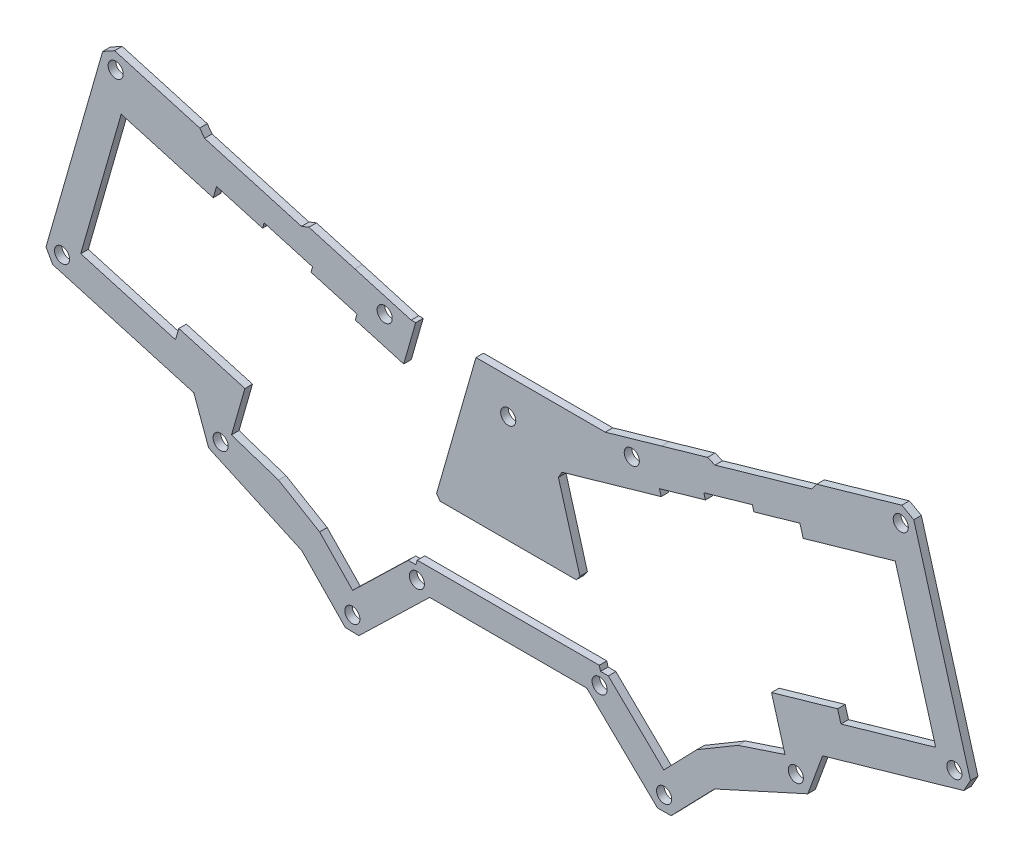
SolidWorks part; units mm, degrees
ref_plane "Plan de face" through (0, 0, 0) normal (0, 0, 1) x (1, 0, 0)
ref_plane "Plan de dessus" through (0, 0, 0) normal (0, 1, 0) x (1, 0, 0)
ref_plane "Plan de droite" through (0, 0, 0) normal (1, 0, 0) x (0, 0, -1)
sketch "Esquisse1" plane through (0, 0, 0) normal (0, 0, 1) x (1, 0, 0)
  line L0 (-121.6461, -32.0475) -> (-108.1875, -28.1884) construction
  line L1 (-108.1875, -28.1884) -> (-104.3283, -41.647) construction
  line L2 (-104.3283, -41.647) -> (-117.7869, -45.5062) construction
  line L3 (-117.7869, -45.5062) -> (-121.6461, -32.0475) construction
  line L4 (-100.1763, -37.9855) -> (-104.0355, -24.5269) construction
  line L5 (-104.0355, -24.5269) -> (-90.5769, -20.6677) construction
  line L6 (-90.5769, -20.6677) -> (-86.7177, -34.1263) construction
  line L7 (-86.7177, -34.1263) -> (-100.1763, -37.9855) construction
  line L8 (-82.5657, -30.4649) -> (-86.4249, -17.0063) construction
  line L9 (-86.4249, -17.0063) -> (-72.9663, -13.1471) construction
  line L10 (-72.9663, -13.1471) -> (-69.1071, -26.6057) construction
  line L11 (-69.1071, -26.6057) -> (-82.5657, -30.4649) construction
  line L12 (-63.6458, -27.5106) -> (-67.505, -14.0519) construction
  line L13 (-67.505, -14.0519) -> (-54.0463, -10.1927) construction
  line L14 (-54.0463, -10.1927) -> (-50.1872, -23.6514) construction
  line L15 (-50.1872, -23.6514) -> (-63.6458, -27.5106) construction
  line L16 (-44.0711, -26.8394) -> (-47.9303, -13.3808) construction
  line L17 (-47.9303, -13.3808) -> (-34.4717, -9.5216) construction
  line L18 (-34.4717, -9.5216) -> (-30.6125, -22.9802) construction
  line L19 (-30.6125, -22.9802) -> (-44.0711, -26.8394) construction
  line L20 (-25.8054, -21.6018) -> (-29.6646, -8.1432) construction
  line L21 (-29.6646, -8.1432) -> (-16.206, -4.284) construction
  line L22 (-16.206, -4.284) -> (-12.3468, -17.7426) construction
  line L23 (-12.3468, -17.7426) -> (-25.8054, -21.6018) construction
  line L24 (-116.4086, -50.3128) -> (-102.95, -46.4536) construction
  line L25 (-102.95, -46.4536) -> (-99.0908, -59.9122) construction
  line L26 (-99.0908, -59.9122) -> (-112.5494, -63.7714) construction
  line L27 (-112.5494, -63.7714) -> (-116.4086, -50.3128) construction
  line L28 (-98.798, -42.7922) -> (-85.3394, -38.933) construction
  line L29 (-85.3394, -38.933) -> (-81.4802, -52.3916) construction
  line L30 (-81.4802, -52.3916) -> (-94.9388, -56.2508) construction
  line L31 (-94.9388, -56.2508) -> (-98.798, -42.7922) construction
  line L32 (-81.1874, -35.2715) -> (-67.7288, -31.4123) construction
  line L33 (-67.7288, -31.4123) -> (-63.8696, -44.8709) construction
  line L34 (-63.8696, -44.8709) -> (-77.3282, -48.7301) construction
  line L35 (-77.3282, -48.7301) -> (-81.1874, -35.2715) construction
  line L36 (-62.2675, -32.3172) -> (-48.8089, -28.458) construction
  line L37 (-48.8089, -28.458) -> (-44.9497, -41.9166) construction
  line L38 (-44.9497, -41.9166) -> (-58.4083, -45.7758) construction
  line L39 (-58.4083, -45.7758) -> (-62.2675, -32.3172) construction
  line L40 (-42.6928, -31.646) -> (-29.2342, -27.7869) construction
  line L41 (-29.2342, -27.7869) -> (-25.375, -41.2455) construction
  line L42 (-25.375, -41.2455) -> (-38.8336, -45.1047) construction
  line L43 (-38.8336, -45.1047) -> (-42.6928, -31.646) construction
  line L44 (-24.4271, -26.4084) -> (-10.9685, -22.5492) construction
  line L45 (-10.9685, -22.5492) -> (-7.1093, -36.0078) construction
  line L46 (-7.1093, -36.0078) -> (-20.5679, -39.867) construction
  line L47 (-20.5679, -39.867) -> (-24.4271, -26.4084) construction
  line L48 (-19.1896, -44.6737) -> (-5.731, -40.8145) construction
  line L49 (-5.731, -40.8145) -> (-1.8718, -54.2731) construction
  line L50 (-1.8718, -54.2731) -> (-15.3304, -58.1323) construction
  line L51 (-15.3304, -58.1323) -> (-19.1896, -44.6737) construction
  line L52 (-37.4554, -49.9113) -> (-23.9967, -46.0521) construction
  line L53 (-23.9967, -46.0521) -> (-20.1376, -59.5107) construction
  line L54 (-20.1376, -59.5107) -> (-33.5962, -63.3699) construction
  line L55 (-33.5962, -63.3699) -> (-37.4554, -49.9113) construction
  line L56 (-57.03, -50.5825) -> (-43.5714, -46.7233) construction
  line L57 (-43.5714, -46.7233) -> (-39.7122, -60.1819) construction
  line L58 (-39.7122, -60.1819) -> (-53.1708, -64.0411) construction
  line L59 (-53.1708, -64.0411) -> (-57.03, -50.5825) construction
  line L60 (-75.9499, -53.5368) -> (-62.4913, -49.6776) construction
  line L61 (-62.4913, -49.6776) -> (-58.6321, -63.1362) construction
  line L62 (-58.6321, -63.1362) -> (-72.0908, -66.9954) construction
  line L63 (-72.0908, -66.9954) -> (-75.9499, -53.5368) construction
  line L64 (-93.5605, -61.0574) -> (-80.1019, -57.1982) construction
  line L65 (-80.1019, -57.1982) -> (-76.2427, -70.6569) construction
  line L66 (-76.2427, -70.6569) -> (-89.7013, -74.516) construction
  line L67 (-89.7013, -74.516) -> (-93.5605, -61.0574) construction
  line L68 (-111.1711, -68.5781) -> (-97.7125, -64.7189) construction
  line L69 (-97.7125, -64.7189) -> (-93.8533, -78.1775) construction
  line L70 (-93.8533, -78.1775) -> (-107.3119, -82.0367) construction
  line L71 (-107.3119, -82.0367) -> (-111.1711, -68.5781) construction
  line L72 (-79.0181, -77.3048) -> (-65.5595, -73.4456) construction
  line L73 (-65.5595, -73.4456) -> (-61.7003, -86.9042) construction
  line L74 (-61.7003, -86.9042) -> (-75.1589, -90.7634) construction
  line L75 (-75.1589, -90.7634) -> (-79.0181, -77.3048) construction
  line L76 (-99.4001, -88.1351) -> (-87.3916, -80.9362)
  line L77 (-87.3916, -80.9362) -> (-80.1927, -92.9448)
  line L78 (-80.1927, -92.9448) -> (-92.2012, -100.1436)
  line L79 (-92.2012, -100.1436) -> (-99.4001, -88.1351)
  line L80 (-120.0498, -100.4367) -> (-110.317, -90.3719)
  line L81 (-110.317, -90.3719) -> (-100.2522, -100.1047)
  line L82 (-100.2522, -100.1047) -> (-109.985, -110.1695)
  line L83 (-109.985, -110.1695) -> (-120.0498, -100.4367)
  line L86 (0.634, -55.7756) -> (-52.9527, -71.1413) construction
  line L89 (-59.2205, -88.2424) -> (-52.9527, -71.1413) construction
  line L96 (-93.4066, -103.0586) -> (-59.4637, -88.3612) construction
  line L97 (-105.418, -115.2057) -> (-93.9754, -103.3509) construction
  line L98 (-126.5332, -96.9919) -> (-107.5003, -115.385) construction
  line L99 (-167.7972, -50.1766) -> (-183.2082, -64.014) construction
  line L100 (-106.3822, -25.4572) -> (-123.6848, -30.4187) construction
  line L101 (-72.1178, -10.6906) -> (-88.4663, -15.3784) construction
  line L102 (-53.2337, -7.6163) -> (-70.5393, -12.5786) construction
  line L103 (-33.6604, -6.9452) -> (-50.9661, -11.9075) construction
  line L104 (-15.3965, -1.7081) -> (-31.745, -6.396) construction
  line L105 (0.5403, -55.2132) -> (-14.6896, -2.0999) construction
  line L106 (-16.199, -60.6113) -> (0.1495, -55.9235) construction
  line L107 (-52.7198, -71.0835) -> (-18.1144, -61.1606) construction
  line L108 (-59.1184, -88.0534) -> (-52.9674, -71.2752) construction
  line L109 (-183.2082, -64.014) -> (-173.1824, -64.9357) construction
  line L113 (-102.2678, -134.438) -> (-84.7238, -116.3191) construction
  line L114 (-84.7238, -116.3191) -> (-47.2969, -99.2981) construction
  line L115 (-47.2969, -99.2981) -> (-41.4917, -83.4594) construction
  line L116 (14.3812, -67.4381) -> (-41.4917, -83.4594) construction
  line L117 (17.8093, -61.2536) -> (-5.1371, 18.7701) construction
  line L122 (-11.3217, 22.1985) -> (-107.4545, -5.3614) construction
  line L129 (-167.7953, -27.6055) -> (-167.7953, -64.7189) construction
  line L130 (-242.0685, -103.8419) -> (-276.37, -88.2424) construction
  line L131 (-229.5108, -116.8112) -> (-242.0685, -103.8419) construction
  line L138 (-208.9328, -96.8551) -> (-229.5108, -116.8112) construction
  line L139 (-225.5107, -79.6567) -> (-208.9328, -96.8551) construction
  line L140 (-109.3352, -134.5492) -> (-102.2678, -134.438) construction
  line L142 (-5.1371, 18.7701) -> (-11.3217, 22.1985) construction
  line L143 (-211.4691, -30.6868) -> (-225.5107, -79.6567) construction
  line L147 (-114.18, -7.2899) -> (-107.4545, -5.3614) construction
  line L148 (-114.18, -7.2899) -> (-123.7936, -10.0465) construction
  line L154 (-118.7579, -16.9241) -> (-12.0005, 13.6817) construction
  line L155 (-131.531, -101.8802) -> (-105.9239, -126.7133) construction
  line L156 (-105.9239, -126.7133) -> (-89.4162, -109.6646) construction
  line L157 (-128.0696, -96.8789) -> (-106.0575, -118.2258)
  line L158 (-106.0575, -118.2258) -> (-92.9354, -104.6737)
  line L161 (1.8709, -56.4612) -> (-35.7408, -67.2462)
  line L162 (1.8709, -56.4612) -> (-14.1861, -0.4639)
  line L163 (-14.1861, -0.4639) -> (-50.7166, -10.9388)
  line L164 (-50.7166, -10.9388) -> (-52.026, -6.3725)
  line L165 (-52.026, -6.3725) -> (-70.2913, -11.61)
  line L166 (-70.2913, -11.61) -> (-70.911, -9.4488)
  line L167 (-70.911, -9.4488) -> (-90.1377, -14.9608)
  line L168 (-90.1377, -14.9608) -> (-89.5177, -17.1231)
  line L169 (-89.5177, -17.1231) -> (-107.783, -22.3606)
  line L170 (-107.783, -22.3606) -> (-107.0938, -24.7639)
  line L171 (-107.0938, -24.7639) -> (-146.5019, -36.064)
  line L174 (-89.4162, -109.6646) -> (-53.6562, -93.4017) construction
  line L175 (-53.6562, -93.4017) -> (-47.6042, -76.8897) construction
  line L176 (9.2923, -60.5749) -> (-47.6042, -76.8897) construction
  line L177 (9.2923, -60.5749) -> (-12.0005, 13.6817) construction
  line L178 (-229.7336, -25.4495) -> (-211.4691, -30.6868) construction
  line L179 (-229.0444, -23.0462) -> (-229.7336, -25.4495) construction
  line L180 (-173.1824, -64.9357) -> (-167.7972, -60.1004) construction
  line L181 (-247.3097, -17.8087) -> (-229.0444, -23.0462) construction
  line L185 (17.8093, -61.2536) -> (14.3812, -67.4381) construction
  line L186 (-183.2987, -65.7677) -> (-173.2729, -66.6895) construction
  line L187 (-173.2729, -66.6895) -> (-167.8052, -74.7882) construction
  line L190 (-246.6897, -15.6465) -> (-247.3097, -17.8087) construction
  line L191 (-263.9939, -10.6857) -> (-246.6897, -15.6465) construction
  line L192 (-264.6136, -12.8469) -> (-263.9939, -10.6857) construction
  line L193 (-282.8789, -7.6094) -> (-264.6136, -12.8469) construction
  line L194 (-284.1883, -12.1757) -> (-282.8789, -7.6094) construction
  line L195 (-320.7188, -1.7008) -> (-284.1883, -12.1757) construction
  line L196 (-336.2245, -55.7756) -> (-320.7188, -1.7008) construction
  line L197 (-183.2987, -65.7677) -> (-167.8052, -88.0782) construction
  line L198 (-181.8414, -71.5322) -> (-174.8684, -81.0171) construction
  line L199 (-174.8684, -81.0171) -> (-178.3549, -83.9622) construction
  line L200 (-344.8828, -60.5749) -> (-323.5901, 13.6817) construction
  line L201 (-344.8828, -60.5749) -> (-287.9863, -76.8897) construction
  line L202 (-281.9343, -93.4017) -> (-287.9863, -76.8897) construction
  line L203 (-246.1743, -109.6646) -> (-281.9343, -93.4017) construction
  line L206 (-228.4967, -24.7639) -> (-209.2751, -30.2756)
  line L207 (-227.8075, -22.3606) -> (-228.4967, -24.7639)
  line L208 (-246.0728, -17.1231) -> (-227.8075, -22.3606)
  line L209 (-245.4528, -14.9608) -> (-246.0728, -17.1231)
  line L210 (-264.6796, -9.4488) -> (-245.4528, -14.9608)
  line L211 (-265.2993, -11.61) -> (-264.6796, -9.4488)
  line L212 (-283.5645, -6.3725) -> (-265.2993, -11.61)
  line L213 (-284.8739, -10.9388) -> (-283.5645, -6.3725)
  line L217 (0.634, -55.7756) -> (-14.8717, -1.7008) construction
  line L220 (-14.8717, -1.7008) -> (-51.4022, -12.1757) construction
  line L221 (-51.4022, -12.1757) -> (-52.7116, -7.6094) construction
  line L222 (-52.7116, -7.6094) -> (-70.9769, -12.8469) construction
  line L223 (-70.9769, -12.8469) -> (-71.5966, -10.6857) construction
  line L224 (-71.5966, -10.6857) -> (-88.9008, -15.6465) construction
  line L225 (-88.9008, -15.6465) -> (-88.2808, -17.8087) construction
  line L226 (-88.2808, -17.8087) -> (-106.5461, -23.0462) construction
  line L227 (-106.5461, -23.0462) -> (-105.8569, -25.4495) construction
  line L228 (-105.8569, -25.4495) -> (-124.1214, -30.6868) construction
  line L231 (-124.1214, -30.6868) -> (-110.0799, -79.6567) construction
  line L232 (-110.0799, -79.6567) -> (-126.6577, -96.8551) construction
  line L233 (-126.6577, -96.8551) -> (-106.0797, -116.8112) construction
  line L234 (-106.0797, -116.8112) -> (-93.522, -103.8419) construction
  line L235 (-93.522, -103.8419) -> (-59.2205, -88.2424) construction
  line L236 (-321.4044, -0.4639) -> (-284.8739, -10.9388)
  line L237 (-337.4614, -56.4612) -> (-321.4044, -0.4639)
  line L238 (-337.4614, -56.4612) -> (-299.8497, -67.2462)
  line L241 (-229.5331, -118.2258) -> (-242.6551, -104.6737)
  line L242 (-208.2366, -97.573) -> (-229.5331, -118.2258)
  line L243 (-229.6666, -126.7133) -> (-246.1743, -109.6646) construction
  line L244 (-204.0596, -101.8802) -> (-229.6666, -126.7133) construction
  line L245 (-331.2803, 15.8863) -> (-208.2299, -19.3904) construction
  line L246 (-178.3549, -83.9622) -> (-185.8788, -75.0552) construction
  line L247 (-185.8788, -75.0552) -> (-181.8414, -71.5322) construction
  line L248 (-176.7625, -46.6332) -> (-185.5498, -54.5291) construction
  line L249 (-185.5498, -54.5291) -> (-181.1562, -59.4188) construction
  line L250 (-181.1562, -59.4188) -> (-172.3689, -51.5229) construction
  line L251 (-276.4721, -88.0534) -> (-282.6232, -71.2752) construction
  line L252 (-282.8707, -71.0835) -> (-317.4761, -61.1606) construction
  line L253 (-319.3915, -60.6113) -> (-335.74, -55.9235) construction
  line L254 (-336.1309, -55.2132) -> (-320.9009, -2.0999) construction
  line L255 (-320.194, -1.7081) -> (-303.8455, -6.396) construction
  line L256 (-301.9301, -6.9452) -> (-284.6245, -11.9075) construction
  line L257 (-282.3568, -7.6163) -> (-265.0512, -12.5786) construction
  line L258 (-263.4727, -10.6906) -> (-247.1242, -15.3784) construction
  line L259 (-229.2083, -25.4572) -> (-211.9057, -30.4187) construction
  line L260 (-172.3689, -51.5229) -> (-176.7625, -46.6332) construction
  line L261 (-209.0573, -96.9919) -> (-228.0902, -115.385) construction
  line L262 (-230.1725, -115.2057) -> (-241.6151, -103.3509) construction
  line L263 (-242.1839, -103.0586) -> (-276.1268, -88.3612) construction
  line L264 (-276.37, -88.2424) -> (-282.6379, -71.1413) construction
  line L265 (-336.2245, -55.7756) -> (-282.6379, -71.1413) construction
  line L268 (-353.3998, -61.2536) -> (-349.9717, -67.4381) construction
  line L274 (-221.4105, -7.2899) -> (-206.0252, -11.7015) construction
  line L275 (-221.4105, -7.2899) -> (-228.136, -5.3614) construction
  line L276 (-330.4534, 18.7701) -> (-324.2688, 22.1985) construction
  line L277 (-226.2553, -134.5492) -> (-233.3227, -134.438) construction
  line L281 (-324.2688, 22.1985) -> (-228.136, -5.3614) construction
  line L282 (-353.3998, -61.2536) -> (-330.4534, 18.7701) construction
  line L283 (-349.9717, -67.4381) -> (-294.0988, -83.4594) construction
  line L284 (-288.2936, -99.2981) -> (-294.0988, -83.4594) construction
  line L285 (-250.8667, -116.3191) -> (-288.2936, -99.2981) construction
  line L286 (-233.3227, -134.438) -> (-250.8667, -116.3191) construction
  line L288 (-225.6055, -110.1695) -> (-215.5407, -100.4367) construction
  line L289 (-235.3383, -100.1047) -> (-225.6055, -110.1695) construction
  line L290 (-225.2735, -90.3719) -> (-235.3383, -100.1047) construction
  line L291 (-215.5407, -100.4367) -> (-225.2735, -90.3719) construction
  line L292 (-243.3893, -100.1436) -> (-236.1904, -88.1351) construction
  line L293 (-255.3978, -92.9448) -> (-243.3893, -100.1436) construction
  line L294 (-248.1989, -80.9362) -> (-255.3978, -92.9448) construction
  line L295 (-236.1904, -88.1351) -> (-248.1989, -80.9362) construction
  line L296 (-260.4316, -90.7634) -> (-256.5724, -77.3048) construction
  line L297 (-273.8902, -86.9042) -> (-260.4316, -90.7634) construction
  line L298 (-270.031, -73.4456) -> (-273.8902, -86.9042) construction
  line L299 (-256.5724, -77.3048) -> (-270.031, -73.4456) construction
  line L300 (-228.2786, -82.0367) -> (-224.4194, -68.5781) construction
  line L301 (-241.7372, -78.1775) -> (-228.2786, -82.0367) construction
  line L302 (-237.878, -64.7189) -> (-241.7372, -78.1775) construction
  line L303 (-224.4194, -68.5781) -> (-237.878, -64.7189) construction
  line L304 (-245.8892, -74.516) -> (-242.03, -61.0574) construction
  line L305 (-259.3478, -70.6569) -> (-245.8892, -74.516) construction
  line L306 (-255.4886, -57.1982) -> (-259.3478, -70.6569) construction
  line L307 (-242.03, -61.0574) -> (-255.4886, -57.1982) construction
  line L308 (-263.4998, -66.9954) -> (-259.6406, -53.5368) construction
  line L309 (-276.9584, -63.1362) -> (-263.4998, -66.9954) construction
  line L310 (-273.0992, -49.6776) -> (-276.9584, -63.1362) construction
  line L311 (-259.6406, -53.5368) -> (-273.0992, -49.6776) construction
  line L312 (-282.4197, -64.0411) -> (-278.5605, -50.5825) construction
  line L313 (-295.8783, -60.1819) -> (-282.4197, -64.0411) construction
  line L314 (-292.0191, -46.7233) -> (-295.8783, -60.1819) construction
  line L315 (-278.5605, -50.5825) -> (-292.0191, -46.7233) construction
  line L316 (-301.9944, -63.3699) -> (-298.1352, -49.9113) construction
  line L317 (-315.453, -59.5107) -> (-301.9944, -63.3699) construction
  line L318 (-311.5938, -46.0521) -> (-315.453, -59.5107) construction
  line L319 (-298.1352, -49.9113) -> (-311.5938, -46.0521) construction
  line L320 (-320.2601, -58.1323) -> (-316.4009, -44.6737) construction
  line L321 (-333.7187, -54.2731) -> (-320.2601, -58.1323) construction
  line L322 (-329.8595, -40.8145) -> (-333.7187, -54.2731) construction
  line L323 (-316.4009, -44.6737) -> (-329.8595, -40.8145) construction
  line L324 (-315.0226, -39.867) -> (-311.1634, -26.4084) construction
  line L325 (-328.4812, -36.0078) -> (-315.0226, -39.867) construction
  line L326 (-324.622, -22.5492) -> (-328.4812, -36.0078) construction
  line L327 (-311.1634, -26.4084) -> (-324.622, -22.5492) construction
  line L328 (-296.7569, -45.1047) -> (-292.8977, -31.646) construction
  line L329 (-310.2155, -41.2455) -> (-296.7569, -45.1047) construction
  line L330 (-306.3563, -27.7869) -> (-310.2155, -41.2455) construction
  line L331 (-292.8977, -31.646) -> (-306.3563, -27.7869) construction
  line L332 (-277.1822, -45.7758) -> (-273.323, -32.3172) construction
  line L333 (-290.6408, -41.9166) -> (-277.1822, -45.7758) construction
  line L334 (-286.7817, -28.458) -> (-290.6408, -41.9166) construction
  line L335 (-273.323, -32.3172) -> (-286.7817, -28.458) construction
  line L336 (-258.2623, -48.7301) -> (-254.4031, -35.2715) construction
  line L337 (-271.7209, -44.8709) -> (-258.2623, -48.7301) construction
  line L338 (-267.8617, -31.4123) -> (-271.7209, -44.8709) construction
  line L339 (-254.4031, -35.2715) -> (-267.8617, -31.4123) construction
  line L340 (-240.6517, -56.2508) -> (-236.7925, -42.7922) construction
  line L341 (-254.1103, -52.3916) -> (-240.6517, -56.2508) construction
  line L342 (-250.2511, -38.933) -> (-254.1103, -52.3916) construction
  line L343 (-236.7925, -42.7922) -> (-250.2511, -38.933) construction
  line L344 (-223.0411, -63.7714) -> (-219.1819, -50.3128) construction
  line L345 (-236.4997, -59.9122) -> (-223.0411, -63.7714) construction
  line L346 (-232.6405, -46.4536) -> (-236.4997, -59.9122) construction
  line L347 (-219.1819, -50.3128) -> (-232.6405, -46.4536) construction
  line L348 (-323.2438, -17.7426) -> (-309.7851, -21.6018) construction
  line L349 (-319.3846, -4.284) -> (-323.2438, -17.7426) construction
  line L350 (-305.926, -8.1432) -> (-319.3846, -4.284) construction
  line L351 (-309.7851, -21.6018) -> (-305.926, -8.1432) construction
  line L352 (-304.978, -22.9802) -> (-291.5194, -26.8394) construction
  line L353 (-301.1188, -9.5216) -> (-304.978, -22.9802) construction
  line L354 (-287.6602, -13.3808) -> (-301.1188, -9.5216) construction
  line L355 (-291.5194, -26.8394) -> (-287.6602, -13.3808) construction
  line L356 (-285.4034, -23.6514) -> (-271.9448, -27.5106) construction
  line L357 (-281.5442, -10.1927) -> (-285.4034, -23.6514) construction
  line L358 (-268.0856, -14.0519) -> (-281.5442, -10.1927) construction
  line L359 (-271.9448, -27.5106) -> (-268.0856, -14.0519) construction
  line L360 (-266.4834, -26.6057) -> (-253.0248, -30.4649) construction
  line L361 (-262.6242, -13.1471) -> (-266.4834, -26.6057) construction
  line L362 (-249.1656, -17.0063) -> (-262.6242, -13.1471) construction
  line L363 (-253.0248, -30.4649) -> (-249.1656, -17.0063) construction
  line L364 (-248.8728, -34.1263) -> (-235.4142, -37.9855) construction
  line L365 (-245.0136, -20.6677) -> (-248.8728, -34.1263) construction
  line L366 (-231.555, -24.5269) -> (-245.0136, -20.6677) construction
  line L367 (-235.4142, -37.9855) -> (-231.555, -24.5269) construction
  line L368 (-217.8036, -45.5062) -> (-213.9444, -32.0475) construction
  line L369 (-231.2622, -41.647) -> (-217.8036, -45.5062) construction
  line L370 (-227.4031, -28.1884) -> (-231.2622, -41.647) construction
  line L371 (-213.9444, -32.0475) -> (-227.4031, -28.1884) construction
  line L372 (-226.2553, -134.5492) -> (-194.0347, -103.3509) construction
  line L373 (-109.3352, -134.5492) -> (-141.5559, -103.3509) construction
  line L374 (-141.5559, -103.3509) -> (-194.0347, -103.3509) construction
  line L375 (-167.7972, -50.1766) -> (-152.3861, -64.014) construction
  line L376 (-162.4119, -64.9357) -> (-167.7972, -60.1004) construction
  line L377 (-162.3376, -66.6895) -> (-167.8052, -74.7882) construction
  line L378 (-152.3118, -65.7677) -> (-167.8052, -88.0782) construction
  line L379 (-163.2254, -51.5229) -> (-158.8318, -46.6332) construction
  line L380 (-154.4381, -59.4188) -> (-163.2254, -51.5229) construction
  line L381 (-150.0445, -54.5291) -> (-154.4381, -59.4188) construction
  line L382 (-158.8318, -46.6332) -> (-150.0445, -54.5291) construction
  line L383 (-149.7316, -75.0552) -> (-153.7691, -71.5322) construction
  line L384 (-157.2555, -83.9622) -> (-149.7316, -75.0552) construction
  line L385 (-160.742, -81.0171) -> (-157.2555, -83.9622) construction
  line L386 (-153.7691, -71.5322) -> (-160.742, -81.0171) construction
  line L387 (-152.3118, -65.7677) -> (-162.3376, -66.6895) construction
  line L388 (-152.3861, -64.014) -> (-162.4119, -64.9357) construction
  line L389 (-206.0252, -11.7015) -> (-129.5654, -11.7015) construction
  line L391 (-209.2751, -30.2756) -> (-204.5226, -13.7015)
  line L394 (-167.1758, -11.7015) -> (-206.0252, -11.7015) construction
  line L395 (-164.5217, -13.7015) -> (-167.1758, -11.7015) construction
  line L396 (-123.7936, -10.0465) -> (-130.6498, -22.4155) construction
  line L399 (-129.5654, -11.7015) -> (-123.7936, -10.0465) construction
  line L400 (-165.8487, -12.7015) -> (-206.1657, -12.7015) construction
  line L401 (-221.6861, -8.2511) -> (-206.1657, -12.7015) construction
  line L402 (-221.6861, -8.2511) -> (-228.4116, -6.3226) construction
  line L403 (-324.1462, 21.1231) -> (-228.4116, -6.3226) construction
  line L404 (-329.6063, 18.0963) -> (-324.1462, 21.1231) construction
  line L405 (-352.3244, -61.1311) -> (-329.6063, 18.0963) construction
  line L406 (-352.3244, -61.1311) -> (-349.2979, -66.591) construction
  line L407 (-349.2979, -66.591) -> (-293.3347, -82.6382) construction
  line L408 (-287.4987, -98.561) -> (-293.3347, -82.6382) construction
  line L409 (-250.2802, -115.4872) -> (-287.4987, -98.561) construction
  line L410 (-232.8926, -133.4446) -> (-250.2802, -115.4872) construction
  line L411 (-226.6535, -133.5428) -> (-232.8926, -133.4446) construction
  line L412 (-226.6535, -133.5428) -> (-194.4395, -102.3509) construction
  line L413 (-141.1511, -102.3509) -> (-194.4395, -102.3509) construction
  line L414 (-108.937, -133.5428) -> (-141.1511, -102.3509) construction
  line L415 (-108.937, -133.5428) -> (-102.6979, -133.4446) construction
  line L416 (-102.6979, -133.4446) -> (-85.3104, -115.4872) construction
  line L417 (-85.3104, -115.4872) -> (-48.0918, -98.561) construction
  line L418 (-48.0918, -98.561) -> (-42.2558, -82.6382) construction
  line L419 (13.7074, -66.591) -> (-42.2558, -82.6382) construction
  line L420 (16.7339, -61.1311) -> (13.7074, -66.591) construction
  line L421 (16.7339, -61.1311) -> (-5.9842, 18.0963) construction
  line L422 (-5.9842, 18.0963) -> (-11.4443, 21.1231) construction
  line L423 (-11.4443, 21.1231) -> (-107.1789, -6.3226) construction
  line L424 (-113.9044, -8.2511) -> (-107.1789, -6.3226) construction
  line L425 (-113.9044, -8.2511) -> (-124.4792, -11.2834) construction
  line L426 (-167.1758, -12.7015) -> (-206.1657, -12.7015) construction
  line L427 (-113.9044, -8.2511) -> (-123.5179, -11.0078) construction
  line L428 (-165.8487, -12.7015) -> (-154.4194, -21.3141) construction
  line L429 (-130.6498, -22.4155) -> (-124.4792, -11.2834) construction
  line L430 (-208.2366, -97.573) -> (-207.4919, -96.8551)
  line L433 (-221.9618, -9.2124) -> (-206.3062, -13.7015)
  line L434 (-129.2843, -13.7015) -> (-180.5957, -13.7015)
  line L435 (-166.1833, -13.7015) -> (-155.2884, -21.9114) construction
  line L436 (-141.5897, -69.6845) -> (-155.2884, -21.9114) construction
  line L437 (-138.3914, -71.4574) -> (-141.5897, -69.6845) construction
  line L438 (-119.7682, -66.1172) -> (-138.3914, -71.4574) construction
  line L439 (-117.9954, -62.9189) -> (-119.7682, -66.1172) construction
  line L440 (-117.9954, -62.9189) -> (-129.5744, -22.538) construction
  line L441 (-129.5744, -22.538) -> (-123.8054, -12.1305) construction
  line L442 (-113.6287, -9.2124) -> (-129.2843, -13.7015)
  line L443 (-113.6287, -9.2124) -> (-106.9033, -7.2839)
  line L444 (-11.5669, 20.0477) -> (-45.3689, 10.3571)
  line L445 (-6.8313, 17.4225) -> (-11.5669, 20.0477)
  line L446 (15.6584, -61.0086) -> (-6.8313, 17.4225)
  line L447 (15.6584, -61.0086) -> (13.0336, -65.7439)
  line L448 (13.0336, -65.7439) -> (-43.0198, -81.817)
  line L449 (-48.8867, -97.824) -> (-43.0198, -81.817)
  line L450 (-85.8969, -114.6554) -> (-48.8867, -97.824)
  line L451 (-103.128, -132.4513) -> (-85.8969, -114.6554)
  line L452 (-108.5388, -132.5364) -> (-103.128, -132.4513)
  line L453 (-108.5388, -132.5364) -> (-136.6152, -105.3509)
  line L454 (-140.7463, -101.3509) -> (-194.8443, -101.3509) construction
  line L455 (-227.0517, -132.5364) -> (-198.9754, -105.3509)
  line L456 (-227.0517, -132.5364) -> (-232.4625, -132.4513)
  line L457 (-232.4625, -132.4513) -> (-249.6936, -114.6554)
  line L458 (-249.6936, -114.6554) -> (-286.7038, -97.824)
  line L459 (-286.7038, -97.824) -> (-292.5707, -81.817)
  line L460 (-348.6241, -65.7439) -> (-292.5707, -81.817)
  line L461 (-351.2489, -61.0086) -> (-348.6241, -65.7439)
  line L462 (-351.2489, -61.0086) -> (-328.7592, 17.4225)
  line L463 (-328.7592, 17.4225) -> (-324.0237, 20.0477)
  line L464 (-324.0237, 20.0477) -> (-228.6872, -7.2839)
  line L465 (-221.9618, -9.2124) -> (-228.6872, -7.2839)
  line L466 (-166.1833, -13.7015) -> (-206.3062, -13.7015) construction
  line L467 (-113.6287, -9.2124) -> (-123.8054, -12.1305) construction
  line L470 (-132.4841, -109.3509) -> (-203.1064, -109.3509) construction
  line L471 (-140.7463, -109.3509) -> (-194.8443, -109.3509) construction
  line L472 (-92.9354, -104.6737) -> (-76.6212, -95.0127)
  line L473 (-227.0517, -132.5364) -> (-194.8443, -101.3509) construction
  line L474 (-108.5388, -132.5364) -> (-140.7463, -101.3509) construction
  line L475 (-76.6212, -95.0127) -> (-57.9612, -88.8254)
  line L476 (-57.9612, -88.8254) -> (-63.3014, -70.2021)
  line L477 (-37.0515, -62.6751) -> (-63.3014, -70.2021)
  line L478 (-37.0515, -62.6751) -> (-35.7408, -67.2462)
  line L479 (-242.6551, -104.6737) -> (-258.9693, -95.0127)
  line L480 (-258.9693, -95.0127) -> (-277.6293, -88.8254)
  line L481 (-277.6293, -88.8254) -> (-272.2891, -70.2021)
  line L482 (-298.539, -62.6751) -> (-272.2891, -70.2021)
  line L483 (-298.539, -62.6751) -> (-299.8497, -67.2462)
  line L484 (-66.4927, 2.2629) -> (-65.3792, -1.6212) construction
  line L485 (-85.7183, -3.2488) -> (-47.2672, 7.7746)
  line L486 (-88.6965, -2.0643) -> (-85.7183, -3.2488)
  line L487 (-45.3689, 10.3571) -> (-47.2672, 7.7746)
  line L488 (-88.6965, -2.0643) -> (-106.9033, -7.2839)
  line L489 (-246.894, -2.0643) -> (-249.8723, -3.2488)
  line L490 (-11.5669, 20.0477) -> (-106.9033, -7.2839) construction
  line L491 (-249.8723, -3.2488) -> (-288.3233, 7.7746)
  line L492 (-290.2216, 10.3571) -> (-288.3233, 7.7746)
  line L493 (-134.5496, -107.3509) -> (-201.0409, -107.3509) construction
  line L494 (-136.6152, -105.3509) -> (-198.9754, -105.3509)
  line L495 (-132.4841, -107.3509) -> (-203.1064, -107.3509) construction
  line L496 (-140.7426, -69.0107) -> (-154.4194, -21.3141) construction
  line L497 (-134.5496, -105.3509) -> (-201.0409, -105.3509) construction
  line L498 (-119.0708, -62.7964) -> (-130.6498, -22.4155) construction
  line L499 (-119.0708, -62.7964) -> (-120.442, -65.2702) construction
  line L500 (-120.442, -65.2702) -> (-138.2688, -70.3819) construction
  line L501 (-138.2688, -70.3819) -> (-140.7426, -69.0107) construction
  line L502 (-213.9586, -46.6087) -> (-210.0994, -33.1501) construction
  line L503 (-204.4396, -96.8551) -> (-203.912, -95.0151)
  line L504 (-191.8496, -52.9484) -> (-182.4136, -20.0412) construction
  line L505 (-207.4919, -96.8551) -> (-204.4396, -96.8551)
  line L506 (-204.5226, -13.7015) -> (-206.3062, -13.7015)
  line L507 (-213.9586, -46.6087) -> (-204.5226, -13.7015) construction
  line L508 (-131.1509, -96.8551) -> (-128.0696, -96.8789)
  line L509 (-131.1509, -96.8551) -> (-131.6785, -95.0151)
  line L510 (-146.5019, -36.064) -> (-147.8731, -38.5378)
  line L511 (-203.912, -95.0151) -> (-131.6785, -95.0151)
  line L512 (-207.4919, -95.0151) -> (-204.4396, -95.0151) construction
  line L513 (-194.7979, -70.2051) -> (-140.7927, -70.2051)
  line L514 (-196.2466, -68.2826) -> (-180.5957, -13.7015)
  line L515 (-203.912, -70.2051) -> (-131.6785, -70.2051) construction
  line L516 (-196.2466, -68.2826) -> (-194.7979, -70.2051)
  line L517 (-139.3439, -68.2826) -> (-147.8731, -38.5378)
  line L518 (-140.7927, -70.2051) -> (-139.3439, -68.2826)
  circle A2 centre (-12.0005, 13.6817) radius 1.6 construction
  circle A3 centre (-12.0005, 13.6817) radius 3
  circle A4 centre (-118.7579, -16.9241) radius 3
  circle A5 centre (9.2923, -60.5749) radius 3
  circle A6 centre (-53.6562, -93.4017) radius 3
  circle A7 centre (-105.9239, -126.7133) radius 3
  circle A8 centre (-131.531, -101.8802) radius 3
  circle A10 centre (-147.4897, -45.973) radius 1.6 construction
  circle A11 centre (-323.5901, 13.6817) radius 3
  circle A12 centre (-188.1008, -45.973) radius 1.6 construction
  circle A14 centre (-204.0596, -101.8802) radius 3
  circle A15 centre (-229.6666, -126.7133) radius 3
  circle A16 centre (-281.9343, -93.4017) radius 3
  circle A17 centre (-344.8828, -60.5749) radius 3
  circle A18 centre (-216.8326, -16.9241) radius 3
  circle A19 centre (-323.5901, 13.6817) radius 1.6 construction
  circle A20 centre (-167.7953, -27.6055) radius 3
  point P138 (-167.7953, -27.6055)
  point P139 (-6.5153, 23.5764)
  point P150 (-169.1046, -23.0392)
  point P200 (19.1875, -66.0599)
  point P203 (-141.5228, -71.3355)
  point P204 (-141.5228, 1.5705)
  point P263 (-133.4062, -12.8029)
  point P264 (-118.5195, -64.7189)
  point P283 (-140.1914, -70.9332)
  point P284 (-157.1758, -11.7015)
  point P405 (-354.778, -66.0599)
  point P406 (-329.0752, 23.5764)
  point P484 (-65.3792, -1.6212)
  point P503 (-148.4244, -36.6152)
  point P506 (-196.7979, -70.2051)
  point P507 (-138.7927, -70.2051)
  dimension "D3" = 3.2
  dimension "D4" = 6
  dimension "D6" = 6
  dimension "D7" = 6
  dimension "D8" = 6
  dimension "D9" = 6
  dimension "D10" = 6
  dimension "D15" = 4
  dimension "D16" = 3.2
  dimension "D14" = 6
  dimension "D5" = 1
  dimension "D17" = 23
  dimension "D22" = 1.84
  dimension "D11" = 1
  dimension "D18" = 8
  dimension "D20" = 2
  dimension "D21" = 2
  dimension "D23" = 24.81
extrude "Boss.-Extru.1" add sketch "Esquisse1" along normal blind 3
sketch "Esquisse2" plane through (0, 0, 3) normal (0, 0, 1) x (1, 0, 0)
  line L0 (-167.7953, -109.3509) -> (-167.7953, -102.3509) construction
  line L1 (-132.4841, -109.3509) -> (-203.1064, -109.3509) construction
  line L2 (-168.7953, -109.3509) -> (-168.7953, -102.3509)
  line L3 (-166.7953, -109.3509) -> (-166.7953, -102.3509)
  line L4 (-163.7953, -109.3509) -> (-163.7953, -102.3509) construction
  line L5 (-164.7953, -109.3509) -> (-164.7953, -102.3509)
  line L6 (-162.7953, -109.3509) -> (-162.7953, -102.3509)
  line L7 (-159.7953, -109.3509) -> (-159.7953, -102.3509) construction
  line L8 (-160.7953, -109.3509) -> (-160.7953, -102.3509)
  line L9 (-158.7953, -109.3509) -> (-158.7953, -102.3509)
  line L10 (-155.7953, -109.3509) -> (-155.7953, -102.3509) construction
  line L11 (-156.7953, -109.3509) -> (-156.7953, -102.3509)
  line L12 (-154.7953, -109.3509) -> (-154.7953, -102.3509)
  line L13 (-151.7953, -109.3509) -> (-151.7953, -102.3509) construction
  line L14 (-152.7953, -109.3509) -> (-152.7953, -102.3509)
  line L15 (-150.7953, -109.3509) -> (-150.7953, -102.3509)
  line L16 (-147.7953, -109.3509) -> (-147.7953, -102.3509) construction
  line L17 (-148.7953, -109.3509) -> (-148.7953, -102.3509)
  line L18 (-146.7953, -109.3509) -> (-146.7953, -102.3509)
  line L19 (-171.7953, -109.3509) -> (-171.7953, -102.3509) construction
  line L20 (-172.7953, -109.3509) -> (-172.7953, -102.3509)
  line L21 (-170.7953, -109.3509) -> (-170.7953, -102.3509)
  line L22 (-175.7953, -109.3509) -> (-175.7953, -102.3509) construction
  line L23 (-176.7953, -109.3509) -> (-176.7953, -102.3509)
  line L24 (-174.7953, -109.3509) -> (-174.7953, -102.3509)
  line L25 (-179.7953, -109.3509) -> (-179.7953, -102.3509) construction
  line L26 (-180.7953, -109.3509) -> (-180.7953, -102.3509)
  line L27 (-178.7953, -109.3509) -> (-178.7953, -102.3509)
  line L28 (-183.7953, -109.3509) -> (-183.7953, -102.3509) construction
  line L29 (-184.7953, -109.3509) -> (-184.7953, -102.3509)
  line L30 (-182.7953, -109.3509) -> (-182.7953, -102.3509)
  line L31 (-187.7953, -109.3509) -> (-187.7953, -102.3509) construction
  line L32 (-188.7953, -109.3509) -> (-188.7953, -102.3509)
  line L33 (-186.7953, -109.3509) -> (-186.7953, -102.3509)
  arc A0 (-168.7953, -109.3509) -> (-166.7953, -109.3509) centre (-167.7953, -109.3509) ccw
  arc A1 (-166.7953, -102.3509) -> (-168.7953, -102.3509) centre (-167.7953, -102.3509) ccw
  arc A2 (-164.7953, -109.3509) -> (-162.7953, -109.3509) centre (-163.7953, -109.3509) ccw
  arc A3 (-162.7953, -102.3509) -> (-164.7953, -102.3509) centre (-163.7953, -102.3509) ccw
  arc A4 (-160.7953, -109.3509) -> (-158.7953, -109.3509) centre (-159.7953, -109.3509) ccw
  arc A5 (-158.7953, -102.3509) -> (-160.7953, -102.3509) centre (-159.7953, -102.3509) ccw
  arc A6 (-156.7953, -109.3509) -> (-154.7953, -109.3509) centre (-155.7953, -109.3509) ccw
  arc A7 (-154.7953, -102.3509) -> (-156.7953, -102.3509) centre (-155.7953, -102.3509) ccw
  arc A8 (-152.7953, -109.3509) -> (-150.7953, -109.3509) centre (-151.7953, -109.3509) ccw
  arc A9 (-150.7953, -102.3509) -> (-152.7953, -102.3509) centre (-151.7953, -102.3509) ccw
  arc A10 (-148.7953, -109.3509) -> (-146.7953, -109.3509) centre (-147.7953, -109.3509) ccw
  arc A11 (-146.7953, -102.3509) -> (-148.7953, -102.3509) centre (-147.7953, -102.3509) ccw
  arc A12 (-172.7953, -109.3509) -> (-170.7953, -109.3509) centre (-171.7953, -109.3509) ccw
  arc A13 (-170.7953, -102.3509) -> (-172.7953, -102.3509) centre (-171.7953, -102.3509) ccw
  arc A14 (-176.7953, -109.3509) -> (-174.7953, -109.3509) centre (-175.7953, -109.3509) ccw
  arc A15 (-174.7953, -102.3509) -> (-176.7953, -102.3509) centre (-175.7953, -102.3509) ccw
  arc A16 (-180.7953, -109.3509) -> (-178.7953, -109.3509) centre (-179.7953, -109.3509) ccw
  arc A17 (-178.7953, -102.3509) -> (-180.7953, -102.3509) centre (-179.7953, -102.3509) ccw
  arc A18 (-184.7953, -109.3509) -> (-182.7953, -109.3509) centre (-183.7953, -109.3509) ccw
  arc A19 (-182.7953, -102.3509) -> (-184.7953, -102.3509) centre (-183.7953, -102.3509) ccw
  arc A20 (-188.7953, -109.3509) -> (-186.7953, -109.3509) centre (-187.7953, -109.3509) ccw
  arc A21 (-186.7953, -102.3509) -> (-188.7953, -102.3509) centre (-187.7953, -102.3509) ccw
  point P4 (-167.7953, -105.8509)
  point P12 (-163.7953, -105.8509)
  point P19 (-159.7953, -105.8509)
  point P26 (-155.7953, -105.8509)
  point P33 (-151.7953, -105.8509)
  point P40 (-147.7953, -105.8509)
  point P47 (-171.7953, -105.8509)
  point P54 (-175.7953, -105.8509)
  point P61 (-179.7953, -105.8509)
  point P68 (-183.7953, -105.8509)
  point P75 (-187.7953, -105.8509)
  dimension "D1" = 6
  dimension "D2" = 6
